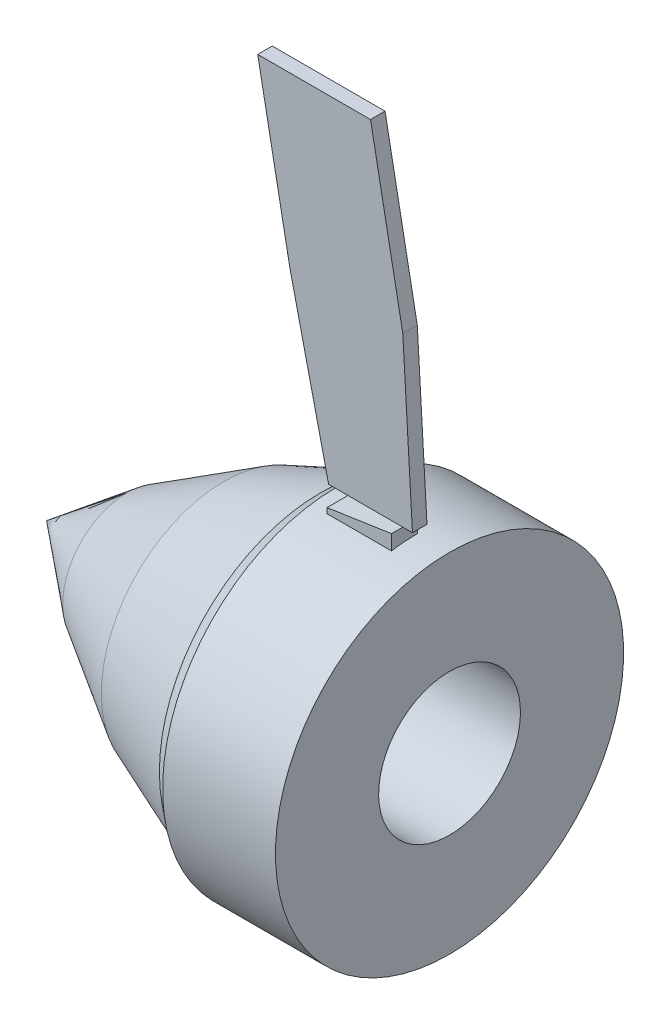
SolidWorks part; units mm, degrees
ref_plane "Front Plane" through (0, 0, 0) normal (0, 0, 1) x (1, 0, 0)
ref_plane "Top Plane" through (0, 0, 0) normal (0, 1, 0) x (1, 0, 0)
ref_plane "Right Plane" through (0, 0, 0) normal (1, 0, 0) x (0, 0, -1)
sketch "Sketch1" plane through (0, 0, 0) normal (0, 0, 1) x (1, 0, 0)
  line L0 (0, 0) -> (1200, 0) construction
  line L1 (0, 0) -> (250, 200)
  line L2 (250, 200) -> (550, 380)
  line L3 (550, 380) -> (850, 500)
  line L4 (850, 500) -> (900, 540)
  line L5 (900, 540) -> (920, 540)
  line L6 (920, 540) -> (920, 460)
  line L7 (920, 460) -> (850, 460)
  line L8 (850, 460) -> (550, 350)
  line L9 (550, 350) -> (250, 170)
  line L10 (250, 170) -> (50, 0)
  line L11 (50, 0) -> (0, 0)
revolve "Revolve1" add sketch "Sketch1" angle 360 about L0
sketch "Sketch2" plane through (0, 0, 0) normal (0, 0, 1) x (1, 0, 0)
  line L0 (0, 0) -> (2000, 0) construction
  line L1 (900, 220) -> (900, 540)
  line L2 (900, 540) -> (900, -540) construction
  line L3 (900, 540) -> (1250, 540)
  line L4 (1250, 540) -> (1250, 220)
  line L5 (1250, 220) -> (900, 220)
revolve "Revolve2" add sketch "Sketch2" angle 360 about L0
sketch "Sketch3" plane through (0, 0, 0) normal (0, 0, 1) x (1, 0, 0)
  line L0 (950, 500) -> (950, 550)
  line L1 (950, 550) -> (1150, 580)
  line L2 (1150, 580) -> (1150, 500)
  line L3 (1150, 500) -> (950, 500)
extrude "Boss-Extrude1" add sketch "Sketch3" along normal blind 80 separate body
sketch "Sketch4" plane through (0, 0, 0) normal (0, 0, 1) x (1, 0, 0)
  line L0 (920, 580) -> (800, 1100)
  line L1 (800, 1100) -> (700, 1625)
  line L2 (700, 1625) -> (1050, 1625)
  line L3 (1050, 1625) -> (1150, 1100)
  line L4 (1150, 1100) -> (1180, 580)
  line L5 (1180, 580) -> (920, 580)
extrude "Boss-Extrude2" add sketch "Sketch4" along normal blind 45 separate body
